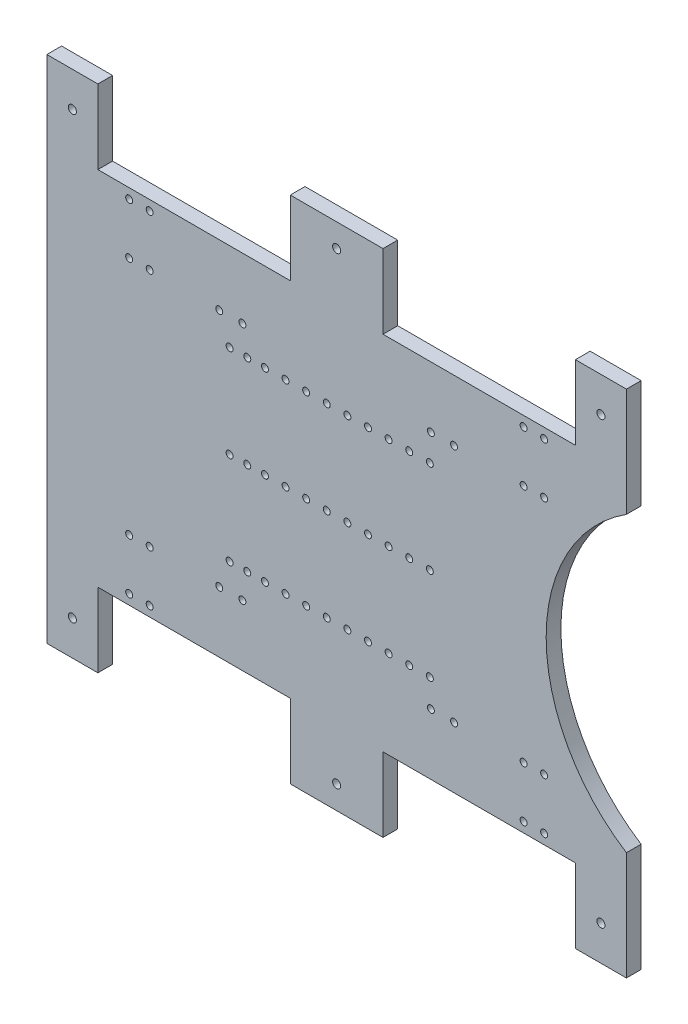
SolidWorks part; units mm, degrees
ref_plane "Front Plane" through (0, 0, 0) normal (0, 0, 1) x (1, 0, 0)
ref_plane "Top Plane" through (0, 0, 0) normal (0, 1, 0) x (1, 0, 0)
ref_plane "Right Plane" through (0, 0, 0) normal (1, 0, 0) x (0, 0, -1)
sketch "Sketch1" plane through (0, 0, 0) normal (0, 0, 1) x (1, 0, 0)
  line L3 (119.6098, 110) -> (97.6098, 110)
  line L8 (-108.3902, 110) -> (-108.3902, 78)
  line L9 (-108.3902, 78) -> (-25.3902, 78)
  line L10 (-25.3902, 110) -> (-25.3902, 78)
  line L11 (14.6098, 110) -> (14.6098, 78)
  line L12 (14.6098, 78) -> (97.6098, 78)
  line L13 (97.6098, 110) -> (97.6098, 78)
  line L14 (-5.3902, 100) -> (-5.3902, -38) construction
  line L21 (-108.3902, 110) -> (-130.3902, 110)
  line L22 (14.6098, 110) -> (-25.3902, 110)
  line L25 (0, 0) -> (-110, 0) construction
  line L58 (-130, 0) -> (-186.6797, 0) construction
  line L60 (119.6098, 110) -> (119.6098, 63.2)
  line L61 (14.6098, -110) -> (-25.3902, -110)
  line L62 (-108.3902, -110) -> (-130.3902, -110)
  line L63 (97.6098, -110) -> (97.6098, -78)
  line L64 (14.6098, -78) -> (97.6098, -78)
  line L65 (14.6098, -110) -> (14.6098, -78)
  line L66 (-25.3902, -110) -> (-25.3902, -78)
  line L67 (-108.3902, -78) -> (-25.3902, -78)
  line L68 (-108.3902, -110) -> (-108.3902, -78)
  line L69 (119.6098, -110) -> (97.6098, -110)
  line L71 (119.6098, -63.2) -> (119.6098, -110)
  line L72 (-130.3902, 110) -> (-130.3902, -110)
  circle A2 centre (-119.3902, 95) radius 1.7525
  circle A3 centre (108.6098, 95) radius 1.7525
  circle A7 centre (-5.3902, 100) radius 1.7525
  circle A8 centre (-5.3902, -100) radius 1.7525
  circle A9 centre (108.6098, -95) radius 1.7525
  circle A10 centre (-119.3902, -95) radius 1.7525
  arc A12 (119.6098, -63.2) -> (119.6098, 63.2) centre (159.9925, 0) cw
  circle A13 centre (-36.3118, 40) radius 1.5
  circle A14 centre (-36.3118, 0) radius 1.5
  circle A15 centre (-36.3118, -40) radius 1.5
  circle A16 centre (-27.4218, -40) radius 1.5
  circle A17 centre (-27.4218, 0) radius 1.5
  circle A18 centre (-27.4218, 40) radius 1.5
  circle A19 centre (-18.5318, -40) radius 1.5
  circle A20 centre (-18.5318, 0) radius 1.5
  circle A21 centre (-18.5318, 40) radius 1.5
  circle A22 centre (-9.6418, -40) radius 1.5
  circle A23 centre (-9.6418, 0) radius 1.5
  circle A24 centre (-9.6418, 40) radius 1.5
  circle A25 centre (-0.7518, -40) radius 1.5
  circle A26 centre (-0.7518, 0) radius 1.5
  circle A27 centre (-0.7518, 40) radius 1.5
  circle A28 centre (8.1382, -40) radius 1.5
  circle A29 centre (8.1382, 0) radius 1.5
  circle A30 centre (8.1382, 40) radius 1.5
  circle A31 centre (17.0282, -40) radius 1.5
  circle A32 centre (17.0282, 0) radius 1.5
  circle A33 centre (17.0282, 40) radius 1.5
  circle A34 centre (25.9182, -40) radius 1.5
  circle A35 centre (25.9182, 0) radius 1.5
  circle A36 centre (25.9182, 40) radius 1.5
  circle A37 centre (34.8082, -40) radius 1.5
  circle A38 centre (34.8082, 0) radius 1.5
  circle A39 centre (34.8082, 40) radius 1.5
  circle A40 centre (-43.9318, 0) radius 1.5
  circle A41 centre (-43.9318, -40) radius 1.5
  circle A42 centre (-43.9318, 40) radius 1.5
  circle A43 centre (-51.5518, 0) radius 1.5
  circle A44 centre (-51.5518, -40) radius 1.5
  circle A45 centre (-51.5518, 40) radius 1.5
  point P0 (0, 0)
  point P20 (-130, 0)
  point P21 (119.2196, 0)
  dimension "D12" = 75
  dimension "D13" = 3.505
  dimension "D16" = 3.505
  dimension "D17" = 20
  dimension "D24" = 3.505
  dimension "D5" = 40
  dimension "D6" = 11
  dimension "D14" = 3
  dimension "D20" = 3
  dimension "D1" = 250
  dimension "D3" = 83
  dimension "D4" = 32
  dimension "D7" = 32
  dimension "D8" = 83
  dimension "D9" = 14.8
  dimension "D10" = 110
  dimension "D11" = 14.8
  dimension "D15" = 15
  dimension "D18" = 10
  dimension "D19" = 40
  dimension "D21" = 9
  dimension "D22" = 11
  dimension "D23" = 15
  dimension "D25" = 3
extrude "Boss-Extrude1" add sketch "Sketch1" along normal blind 6.35
sketch "Sketch3" plane through (0, 0, 6.35) normal (0, 0, 1) x (1, 0, 0)
  line L0 (-25.3902, 78) -> (-108.3902, 78) construction
  line L1 (-90.8902, 78) -> (-80.8902, 78) construction
  line L2 (-90.8902, 78) -> (-90.8902, 46.7) construction
  line L4 (-80.8902, 78) -> (-80.8902, 56.7) construction
  line L5 (-108.3902, 78) -> (-108.3902, 110) construction
  line L6 (-80.8902, 56.7) -> (-51.0402, 56.7) construction
  line L9 (-51.0402, 56.7) -> (-51.0402, 46.7) construction
  line L10 (-90.8902, 46.7) -> (-51.0402, 46.7) construction
  line L11 (-5.3902, 100) -> (-5.3902, 0) construction
  line L12 (-5.3902, 0) -> (-125.0363, 0) construction
  line L13 (-51.0402, -56.7) -> (-51.0402, -46.7) construction
  line L14 (-80.8902, -56.7) -> (-51.0402, -56.7) construction
  line L15 (-80.8902, -78) -> (-80.8902, -56.7) construction
  line L16 (-90.8902, -78) -> (-90.8902, -46.7) construction
  line L17 (-90.8902, -78) -> (-80.8902, -78) construction
  line L18 (80.1098, -78) -> (80.1098, -46.7) construction
  line L19 (70.1098, -78) -> (70.1098, -56.7) construction
  line L20 (70.1098, -56.7) -> (40.2598, -56.7) construction
  line L21 (40.2598, -56.7) -> (40.2598, -46.7) construction
  line L22 (80.1098, 46.7) -> (40.2598, 46.7) construction
  line L23 (40.2598, 56.7) -> (40.2598, 46.7) construction
  line L24 (70.1098, 56.7) -> (40.2598, 56.7) construction
  line L25 (70.1098, 78) -> (70.1098, 56.7) construction
  line L26 (80.1098, 78) -> (80.1098, 46.7) construction
  line L27 (80.1098, 78) -> (70.1098, 78) construction
  line L28 (40.2598, -46.7) -> (80.1098, -46.7) construction
  line L29 (-90.8902, -46.7) -> (-51.0402, -46.7) construction
  circle A0 centre (-86.0402, 73.7) radius 1.5
  circle A1 centre (-86.0402, 51.7) radius 1.5
  circle A2 centre (-56.0402, 51.7) radius 1.5
  circle A3 centre (-56.0402, -51.7) radius 1.5
  circle A4 centre (-86.0402, -51.7) radius 1.5
  circle A5 centre (-86.0402, -73.7) radius 1.5
  circle A6 centre (75.2598, -73.7) radius 1.5
  circle A7 centre (75.2598, -51.7) radius 1.5
  circle A8 centre (45.2598, -51.7) radius 1.5
  circle A9 centre (45.2598, 51.7) radius 1.5
  circle A10 centre (75.2598, 51.7) radius 1.5
  circle A11 centre (75.2598, 73.7) radius 1.5
  circle A12 centre (-46.0402, 51.7) radius 1.5
  circle A13 centre (-94.8902, 51.7) radius 1.5
  circle A14 centre (-94.8902, 73.7) radius 1.5
  circle A15 centre (-46.0402, -51.7) radius 1.5
  circle A16 centre (-94.8902, -51.7) radius 1.5
  circle A17 centre (-94.8902, -73.7) radius 1.5
  circle A18 centre (35.2598, 51.7) radius 1.5
  circle A19 centre (84.1098, 51.7) radius 1.5
  circle A20 centre (84.1098, 73.7) radius 1.5
  circle A21 centre (84.1098, -73.7) radius 1.5
  circle A22 centre (35.2598, -51.7) radius 1.5
  circle A23 centre (84.1098, -51.7) radius 1.5
  point P63 (0, 0)
  point P64 (0, 0)
  point P65 (0, 0)
  point P66 (0, 0)
  point P67 (0, 0)
  point P68 (0, 0)
  dimension "D6" = 3
  dimension "D11" = 3
  dimension "D13" = 3
  dimension "D14" = 8.85
  dimension "D1" = 17.5
  dimension "D2" = 10
  dimension "D3" = 10
  dimension "D4" = 31.3
  dimension "D5" = 39.85
  dimension "D7" = 22
  dimension "D8" = 30
  dimension "D9" = 5
  dimension "D10" = 5
  dimension "D12" = 10
extrude "Cut-Extrude2" cut sketch "Sketch3" against normal blind 10
